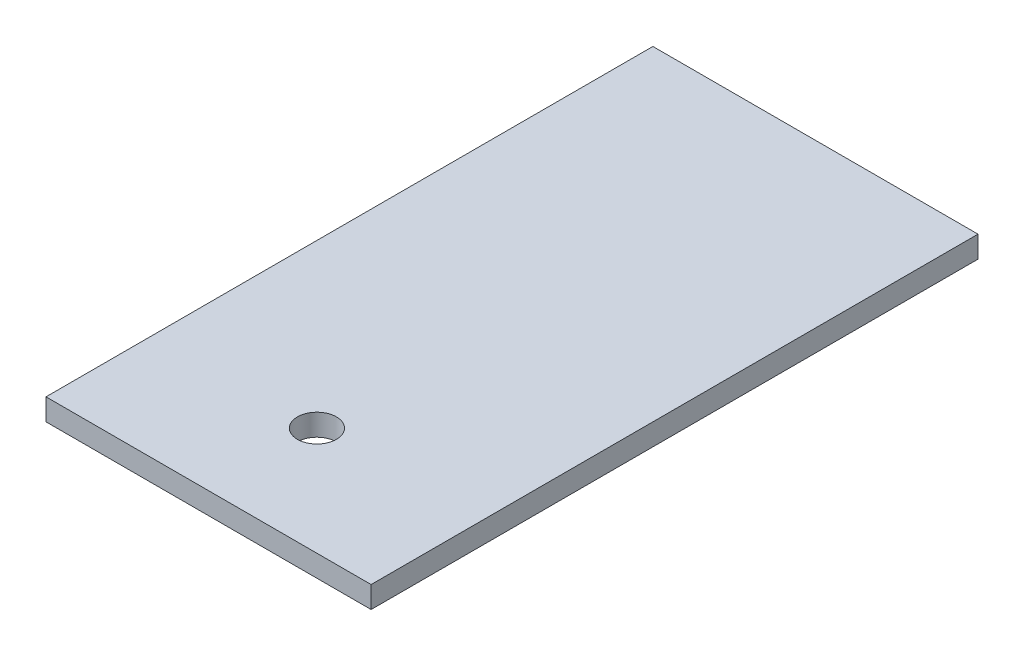
SolidWorks part; units mm, degrees
material "Cedar"
ref_plane "Front Plane" through (0, 0, 0) normal (0, 0, 1) x (1, 0, 0)
ref_plane "Top Plane" through (0, 0, 0) normal (0, 1, 0) x (1, 0, 0)
ref_plane "Right Plane" through (0, 0, 0) normal (1, 0, 0) x (0, 0, -1)
sketch "Sketch1" plane through (0, 0, 0) normal (0, 1, 0) x (1, 0, 0)
  line L0 (-75, -140) -> (75, 140) construction
  line L1 (-75, -140) -> (75, -140)
  line L2 (-75, -140) -> (-75, 140)
  line L3 (-75, 140) -> (75, 140)
  line L4 (75, -140) -> (75, 140)
  line L5 (75, -140) -> (-75, 140) construction
  circle A0 centre (0, -90) radius 9
  point P4 (0, 0)
  dimension "D3" = 18
  dimension "D1" = 150
  dimension "D2" = 280
  dimension "D4" = 50
extrude "Boss-Extrude1" add sketch "Sketch1" along normal blind 10
